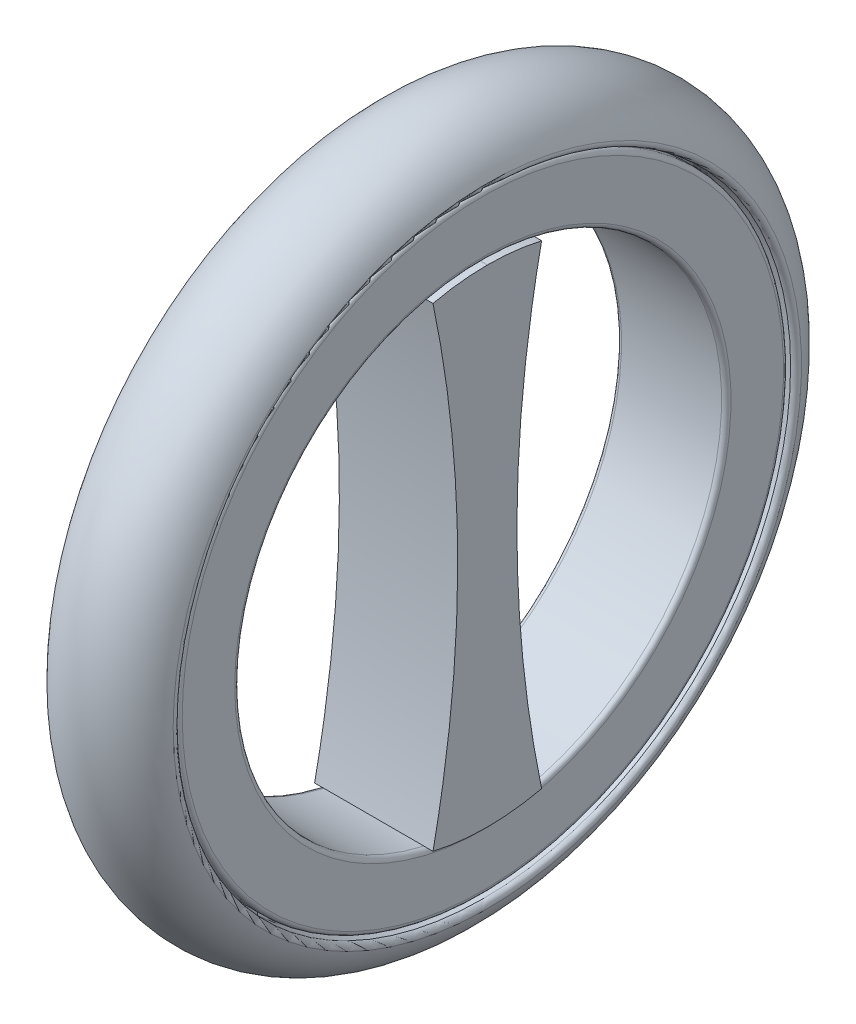
SolidWorks part; units mm, degrees
ref_plane "Front Plane" through (0, 0, 0) normal (0, 0, 1) x (1, 0, 0)
ref_plane "Top Plane" through (0, 0, 0) normal (0, 1, 0) x (1, 0, 0)
ref_plane "Right Plane" through (0, 0, 0) normal (1, 0, 0) x (0, 0, -1)
ref_axis "Axis1" through (-27.5, 0, 0) along (1, 0, 0)
sketch "Sketch2" plane through (0, 0, 0) normal (1, 0, 0) x (0, 0, -1)
  circle A0 centre (0, 0) radius 100
  circle A1 centre (0, 0) radius 87.7772
sketch "Sketch6" plane through (0, 0, 0) normal (0, 0, 1) x (1, 0, 0)
  line L0 (0, -100) -> (0, 100) construction
  line L4 (0, 123.2928) -> (0, 109.4274) construction
  line L5 (-23.1278, 129.9846) -> (-16.2746, 129.9846)
  line L6 (12.2746, 123.2928) -> (-12.2746, 123.2928)
  line L7 (-14.2746, 125.2928) -> (-14.2746, 127.9846)
  line L8 (23.1278, 129.9846) -> (16.2746, 129.9846)
  line L9 (14.2746, 125.2928) -> (14.2746, 127.9846)
  line L10 (-21.1278, 128.9846) -> (-16.2746, 128.9846)
  line L11 (-15.2746, 125.2928) -> (-15.2746, 127.9846)
  line L12 (12.2746, 122.2928) -> (-12.2746, 122.2928)
  line L13 (15.2746, 125.2928) -> (15.2746, 127.9846)
  line L14 (21.1278, 128.9846) -> (16.2746, 128.9846)
  line L15 (-12.2746, 102.8016) -> (12.2746, 102.8016)
  line L16 (12.2746, 102.8016) -> (21.1278, 102.8016)
  line L17 (23.1278, 104.8016) -> (23.1278, 126.9846)
  line L18 (-12.2746, 102.8016) -> (-21.1278, 102.8016)
  line L19 (-23.1278, 104.8016) -> (-23.1278, 126.9846)
  line L20 (-23.1278, 128.9846) -> (-16.2746, 128.9846) construction
  line L21 (23.1278, 128.9846) -> (16.2746, 128.9846) construction
  arc A0 (-25, 132.6882) -> (25, 132.6882) centre (0, 123.2928) cw
  arc A1 (-14.2746, 127.9846) -> (-16.2746, 129.9846) centre (-16.2746, 127.9846) ccw
  arc A2 (-12.2746, 123.2928) -> (-14.2746, 125.2928) centre (-12.2746, 125.2928) cw
  arc A3 (-23.1278, 129.9846) -> (-25, 132.6882) centre (-23.1278, 131.9846) cw
  arc A4 (23.1278, 104.8016) -> (21.1278, 102.8016) centre (21.1278, 104.8016) cw
  arc A5 (12.2746, 123.2928) -> (14.2746, 125.2928) centre (12.2746, 125.2928) ccw
  arc A6 (14.2746, 127.9846) -> (16.2746, 129.9846) centre (16.2746, 127.9846) cw
  arc A7 (23.1278, 129.9846) -> (25, 132.6882) centre (23.1278, 131.9846) ccw
  arc A8 (-15.2746, 127.9846) -> (-16.2746, 128.9846) centre (-16.2746, 127.9846) ccw
  arc A9 (-12.2746, 122.2928) -> (-15.2746, 125.2928) centre (-12.2746, 125.2928) cw
  arc A10 (12.2746, 122.2928) -> (15.2746, 125.2928) centre (12.2746, 125.2928) ccw
  arc A11 (15.2746, 127.9846) -> (16.2746, 128.9846) centre (16.2746, 127.9846) cw
  arc A12 (21.1278, 128.9846) -> (23.1278, 126.9846) centre (21.1278, 126.9846) cw
  arc A13 (-23.1278, 104.8016) -> (-21.1278, 102.8016) centre (-21.1278, 104.8016) ccw
  arc A14 (-21.1278, 128.9846) -> (-23.1278, 126.9846) centre (-21.1278, 126.9846) ccw
  arc A15 (23.1278, 128.9846) -> (25.9361, 133.04) centre (23.1278, 131.9846) ccw construction
  point P2 (0, 150)
  dimension "D1" = 2
  dimension "D2" = 2
  dimension "D3" = 2
  dimension "D8" = 2
  dimension "D9" = 2
  dimension "D4" = 50
  dimension "D5" = 26.7072
  dimension "D6" = 26.7072
  dimension "D7" = 150
revolve "Revolve3" add sketch "Sketch6" angle 360 about axis through (-27.5, 0, 0) along (1, 0, 0)
sketch "Sketch7" plane through (0, 0, 0) normal (1, 0, 0) x (0, 0, -1)
  line L0 (0, 0) -> (0, 102.8016) construction
  line L1 (0, 0) -> (0, -102.8016) construction
  circle A0 centre (0, 0) radius 102.8016 construction
  circle A2 centre (0, 0) radius 102.8016 construction
  spline S0 degree 2 poles (-22.9426, 100.2088) (-2.0594, 0) (-22.9427, -100.2088) knots 0 0 0 1 1 1
  spline S1 degree 2 poles (-22.9426, 100.2088) (-11.6094, 102.7983) (0, 102.8016) knots 0 0 0 1 1 1
  spline S2 degree 2 poles (-22.9427, -100.2088) (-11.5883, -102.8001) (0, -102.8016) knots 0 0 0 1 1 1
  spline S3 degree 2 poles (22.9427, -100.2088) (11.5883, -102.8001) (0, -102.8016) knots 0 0 0 1 1 1
  spline S4 degree 2 poles (22.9426, 100.2088) (11.6094, 102.7983) (0, 102.8016) knots 0 0 0 1 1 1
  spline S5 degree 2 poles (22.9426, 100.2088) (2.0594, 0) (22.9427, -100.2088) knots 0 0 0 1 1 1
  point P19 (0, 0)
extrude "Boss-Extrude2" add sketch "Sketch7" along normal blind 25 and the other way blind 25 separate body
